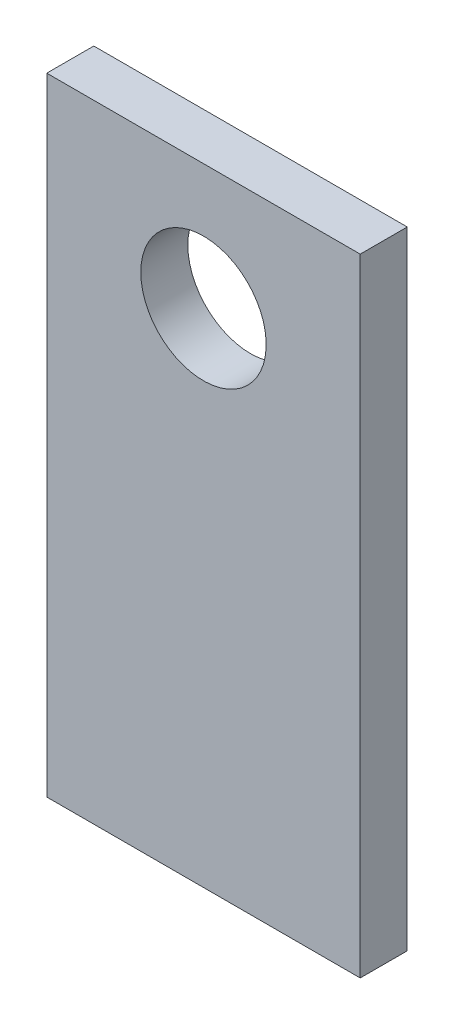
SolidWorks part; units mm, degrees
ref_plane "Front Plane" through (0, 0, 0) normal (0, 0, 1) x (1, 0, 0)
ref_plane "Top Plane" through (0, 0, 0) normal (0, 1, 0) x (1, 0, 0)
ref_plane "Right Plane" through (0, 0, 0) normal (1, 0, 0) x (0, 0, -1)
sketch "Sketch1" plane through (0, 0, 0) normal (0, 0, 1) x (1, 0, 0)
  line L0 (0, 50.8) -> (63.5, 50.8) construction
  line L1 (0, 0) -> (63.5, 0)
  line L2 (0, 0) -> (0, 127)
  line L3 (0, 127) -> (63.5, 127)
  line L4 (63.5, 0) -> (63.5, 127)
  circle A0 centre (31.75, 101.6) radius 12.7
  dimension "D3" = 25.4
  dimension "D1" = 63.5
  dimension "D2" = 127
  dimension "D4" = 50.8
  dimension "D5" = 31.75
  dimension "D6" = 50.8
extrude "Boss-Extrude1" add sketch "Sketch1" along normal blind 9.525
